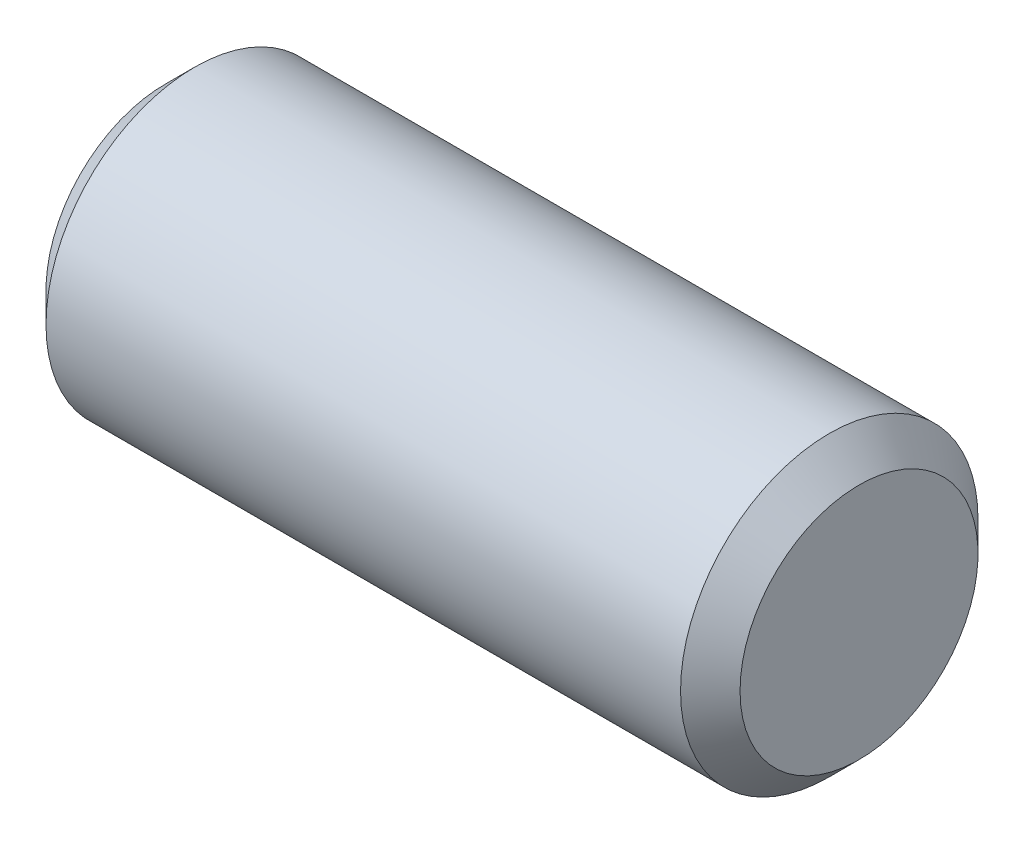
SolidWorks part; units mm, degrees
ref_plane "Front" through (0, 0, 0) normal (0, 0, 1) x (1, 0, 0)
ref_plane "Top" through (0, 0, 0) normal (0, 1, 0) x (1, 0, 0)
ref_plane "Right" through (0, 0, 0) normal (1, 0, 0) x (0, 0, -1)
sketch "Sketch1" plane through (0, 0, 0) normal (0, 0, 1) x (1, 0, 0)
  line L0 (-5.5562, 0) -> (5.5562, 0) construction
  line L1 (5.5562, 2.3813) -> (5.5562, -2.3813) construction
  line L2 (-5.5562, 2.3813) -> (-5.5562, -2.3813) construction
  dimension "Length" = 11.1125
  dimension "Diameter" = 4.7625
sketch "Sketch2" plane through (0, 0, 0) normal (1, 0, 0) x (0, 0, -1)
  circle A0 centre (0, 0) radius 2.3813
extrude "Extrude1" add sketch "Sketch2" against normal up to vertex (5.5563 mm away) and the other way up to vertex (5.5563 mm away) up to point (-5.5562, 2.3813, 0) other way up to point (5.5562, 2.3813, 0)
chamfer "Chamfer1" distance 0.4763 angle 45 2 edges at (5.5562, 0, -2.3813) (-5.5562, 0, -2.3813)
equation "\"D1@Chamfer1\" = \"Diameter@Sketch1\"*.1"
